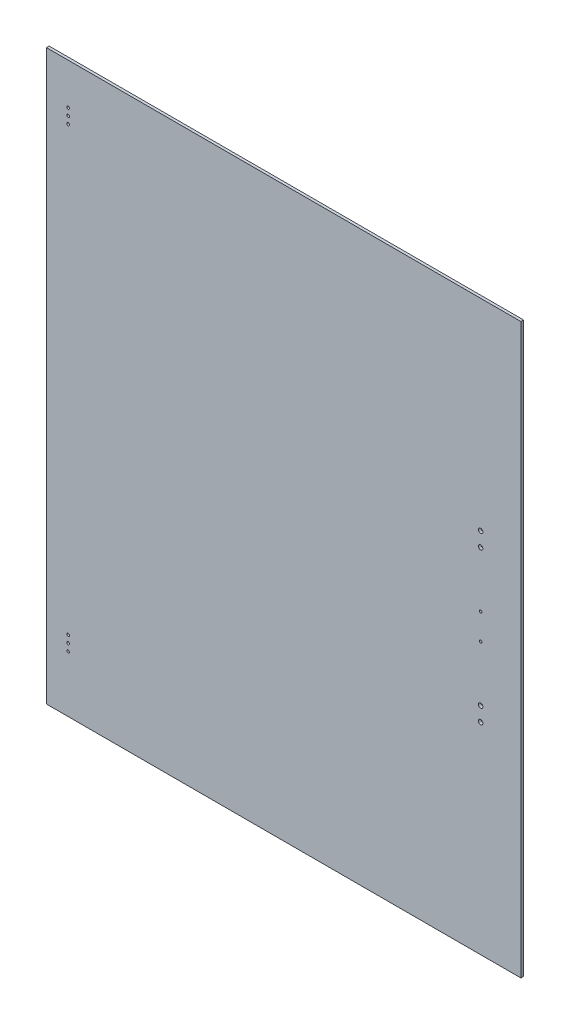
SolidWorks part; units mm, degrees
material "Acrylic (Medium-high impact)"
ref_plane "Front Plane" through (0, 0, 0) normal (0, 0, 1) x (1, 0, 0)
ref_plane "Top Plane" through (0, 0, 0) normal (0, 1, 0) x (1, 0, 0)
ref_plane "Right Plane" through (0, 0, 0) normal (1, 0, 0) x (0, 0, -1)
sketch "Sketch1" plane through (0, 0, 0) normal (0, 0, 1) x (1, 0, 0)
  line L1 (-476.5049, 294.7573) -> (53.4951, 294.7573)
  line L2 (-476.5049, 294.7573) -> (-476.5049, -340.2427)
  line L3 (-476.5049, -340.2427) -> (53.4951, -340.2427)
  line L4 (53.4951, 294.7573) -> (53.4951, -340.2427)
  dimension "D1" = 635
  dimension "D2" = 530
extrude "Boss-Extrude1" add sketch "Sketch1" along normal blind 3
sketch "Sketch2" plane through (0, 0, 3) normal (0, 0, 1) x (1, 0, 0)
  line L0 (-476.5049, 294.7573) -> (-476.5049, -340.2427) construction
  line L1 (53.4951, 294.7573) -> (-476.5049, 294.7573) construction
  line L2 (-476.5049, -340.2427) -> (53.4951, -340.2427) construction
  circle A0 centre (-452.2449, 248.7573) radius 1.5
  circle A1 centre (-452.2449, 240.7573) radius 1.5
  circle A2 centre (-452.2449, 232.7573) radius 1.5
  circle A3 centre (-452.2449, -261.2427) radius 1.5
  circle A4 centre (-452.2449, -269.2427) radius 1.5
  circle A5 centre (-452.2449, -277.2427) radius 1.5
  dimension "D1" = 3
  dimension "D4" = 8
  dimension "D5" = 24.26
  dimension "D6" = 8
  dimension "D7" = 24.26
  dimension "D8" = 3
  dimension "D11" = 63
  dimension "D12" = 24.26
  dimension "D2" = 24.26
  dimension "D3" = 46
  dimension "D9" = 8
  dimension "D10" = 8
extrude "Cut-Extrude1" cut sketch "Sketch2" against normal through all
sketch "Sketch3" plane through (0, 0, 3) normal (0, 0, 1) x (1, 0, 0)
  line L0 (-476.5049, -22.7427) -> (53.4951, -22.7427) construction
  line L1 (-476.5049, 294.7573) -> (-476.5049, -340.2427) construction
  line L2 (53.4951, -340.2427) -> (53.4951, 294.7573) construction
  line L3 (8.4951, -340.2427) -> (8.4951, 294.7573) construction
  line L4 (-476.5049, -340.2427) -> (53.4951, -340.2427) construction
  line L5 (53.4951, 294.7573) -> (-476.5049, 294.7573) construction
  circle A0 centre (8.4951, 69.7573) radius 2.5
  circle A1 centre (8.4951, 53.7573) radius 2.5
  circle A2 centre (8.4951, -99.2427) radius 2.5
  circle A3 centre (8.4951, -115.2427) radius 2.5
  circle A4 centre (8.4951, -37.2427) radius 1.5
  circle A5 centre (8.4951, -8.2427) radius 1.5
  dimension "D1" = 5
  dimension "D2" = 5
  dimension "D3" = 16
  dimension "D4" = 5
  dimension "D5" = 5
  dimension "D6" = 16
  dimension "D7" = 185
  dimension "D8" = 92.5
  dimension "D9" = 45
  dimension "D10" = 45
  dimension "D11" = 45
  dimension "D12" = 45
  dimension "D13" = 3
  dimension "D14" = 3
  dimension "D15" = 29
  dimension "D16" = 14.5
extrude "Cut-Extrude2" cut sketch "Sketch3" against normal through all
